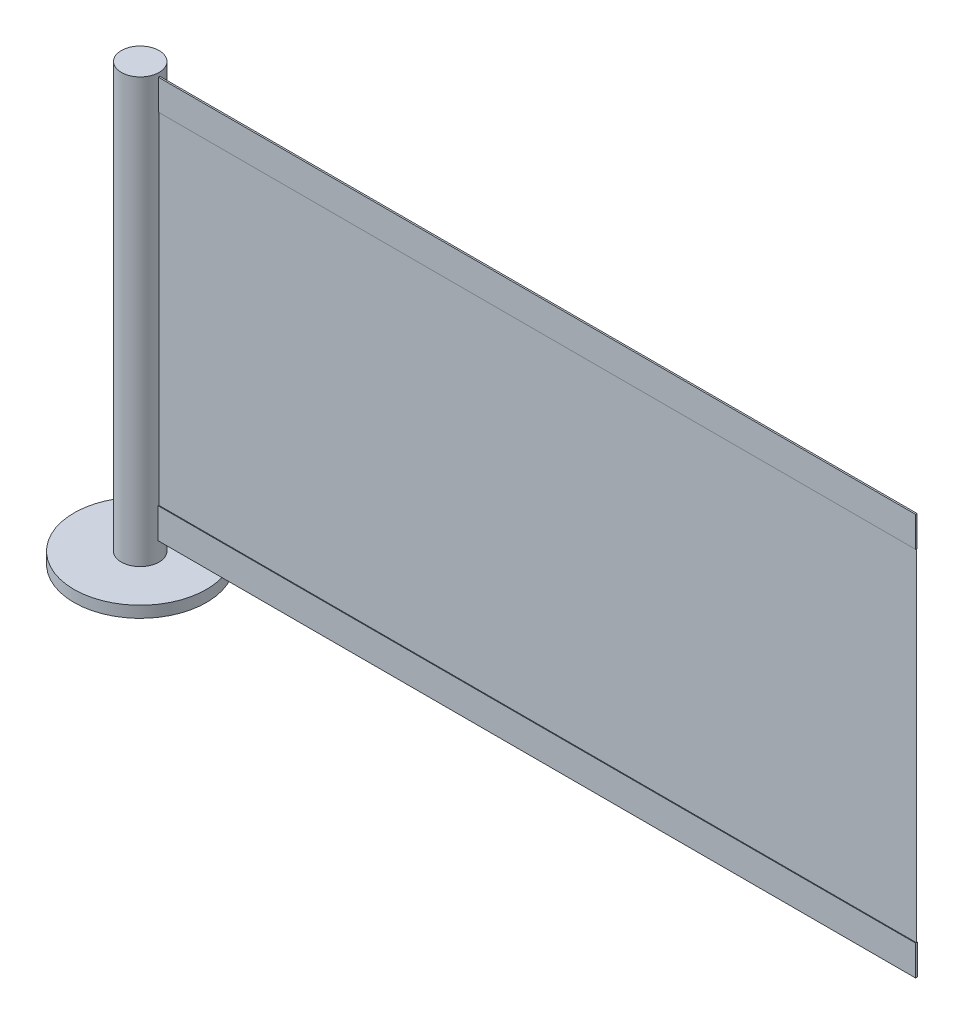
SolidWorks part; units mm, degrees
ref_plane "Front Plane" through (0, 0, 0) normal (0, 0, 1) x (1, 0, 0)
ref_plane "Top Plane" through (0, 0, 0) normal (0, 1, 0) x (1, 0, 0)
ref_plane "Right Plane" through (0, 0, 0) normal (1, 0, 0) x (0, 0, -1)
sketch "Sketch2" plane through (0, 0, 0) normal (0, 1, 0) x (1, 0, 0)
  circle A0 centre (0, 0) radius 175
extrude "Boss-Extrude1" add sketch "Sketch2" along normal blind 30
sketch "Sketch3" plane through (0, 30, 0) normal (0, 1, 0) x (1, 0, 0)
  circle A1 centre (0, 0) radius 50
extrude "Boss-Extrude2" add sketch "Sketch3" along normal blind 1110
sketch "Sketch7" plane through (0, 1140, 0) normal (0, 1, 0) x (1, 0, 0)
  line L0 (0, -0.5) -> (0, 0.5) construction
  line L2 (0, -0.5) -> (2050, -0.5)
  line L3 (0, -0.5) -> (0, 0.5)
  line L4 (0, 0.5) -> (2050, 0.5)
  line L5 (2050, -0.5) -> (2050, 0.5)
  point P5 (0, 0)
  dimension "D1" = 1
  dimension "D2" = 2050
extrude "Boss-Extrude3" add sketch "Sketch7" against normal blind 1060
sketch "Sketch8" plane through (0, 1140, 0) normal (0, 1, 0) x (1, 0, 0)
  line L0 (0, -2) -> (0, 2) construction
  line L2 (0, -2) -> (2050, -2)
  line L3 (0, -2) -> (0, 2)
  line L4 (0, 2) -> (2050, 2)
  line L5 (2050, -2) -> (2050, 2)
  point P4 (0, 0)
  dimension "D1" = 4
  dimension "D2" = 2050
extrude "Boss-Extrude4" add sketch "Sketch8" against normal blind 80
sketch3d "3DSketch2"
  line L0 (2050, 80, 0.5) -> (2050, 80, -0.5) construction
  line L1 (2050, 80, -0.5) -> (49.9975, 80, -0.5) construction
sketch "Sketch11" plane through (0, 80, 0) normal (0, -1, 0) x (-1, 0, 0)
  line L0 (-2050, -2.4692) -> (-2050, 2.4692) construction
  line L2 (-2050, -0.5) -> (-2050, 0.5) construction
  line L4 (-2050, -2.4692) -> (0, -2.4692)
  line L5 (-2050, -2.4692) -> (-2050, 2.4692)
  line L6 (-2050, 2.4692) -> (0, 2.4692)
  line L7 (0, -2.4692) -> (0, 2.4692)
  point P3 (-2050, 0)
  dimension "D1" = 2050
extrude "Boss-Extrude5" add sketch "Sketch11" against normal blind 80
sketch "Sketch12" plane through (0, 1140, 0) normal (0, 1, 0) x (1, 0, 0)
  circle A0 centre (0, 0) radius 50
extrude "Boss-Extrude6" add sketch "Sketch12" along normal blind 10
